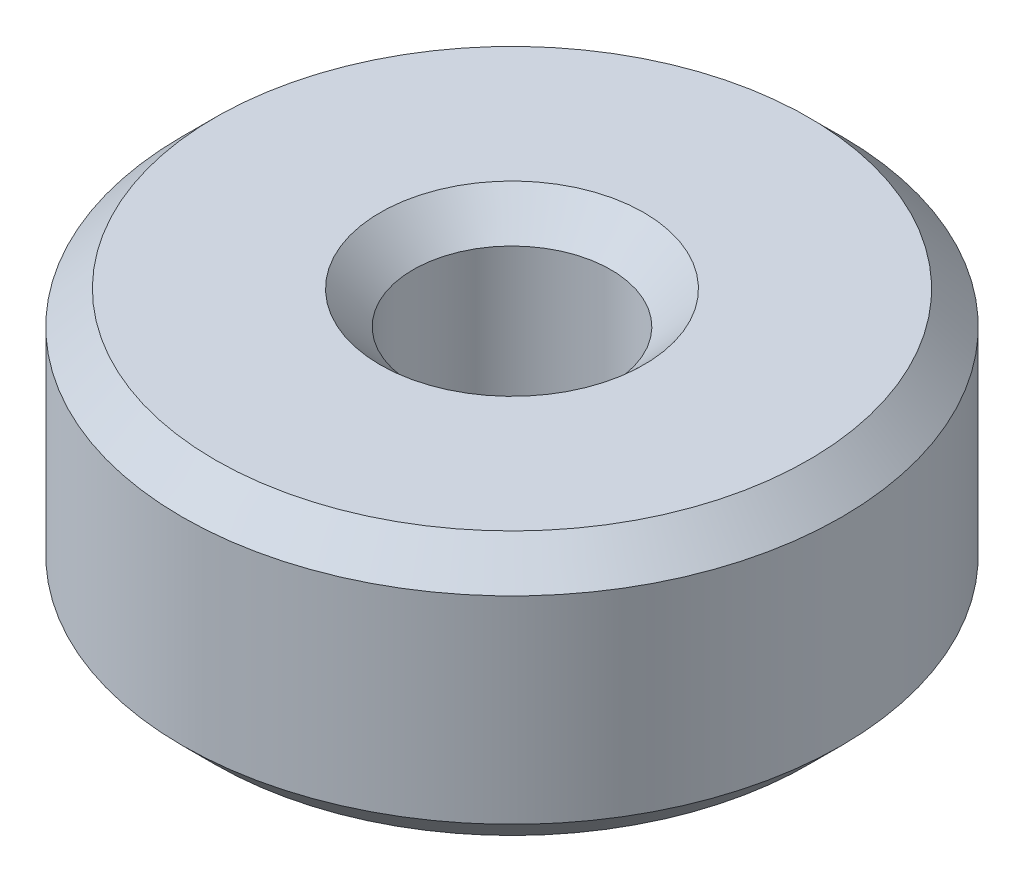
SolidWorks part; units mm, degrees
ref_plane "前视基准面" through (0, 0, 0) normal (0, 0, 1) x (1, 0, 0)
ref_plane "上视基准面" through (0, 0, 0) normal (0, 1, 0) x (1, 0, 0)
ref_plane "右视基准面" through (0, 0, 0) normal (1, 0, 0) x (0, 0, -1)
sketch "草图1" plane through (0, 0, 0) normal (0, 1, 0) x (1, 0, 0)
  circle A0 centre (0, 0) radius 5
  circle A1 centre (0, 0) radius 1.5
extrude "凸台-拉伸1" add sketch "草图1" along normal blind 4
chamfer "倒角1" distance 0.5 angle 45 3 edges at (0, 0, 5) (0, 4, 5) (0, 4, 1.5)
